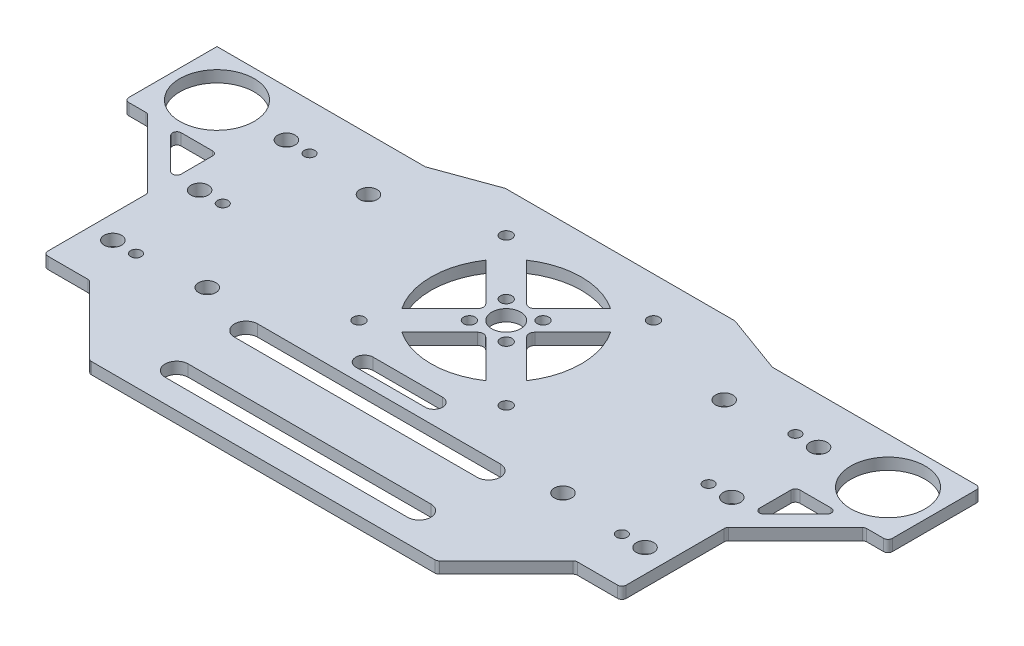
SolidWorks part; units mm, degrees
ref_plane "前视基准面" through (0, 0, 0) normal (0, 0, 1) x (1, 0, 0)
ref_plane "上视基准面" through (0, 0, 0) normal (0, 1, 0) x (1, 0, 0)
ref_plane "右视基准面" through (0, 0, 0) normal (1, 0, 0) x (0, 0, -1)
other "Configuration Table"
sketch "草图1" plane through (0, 0, 0) normal (0, 1, 0) x (1, 0, 0)
  line L0 (-50, 23) -> (50, 23)
  line L1 (50, 23) -> (50, -23)
  line L2 (50, -23) -> (-50, -23)
  line L3 (-50, -23) -> (-50, 23)
  line L5 (0, 23) -> (0, -23) construction
  line L6 (3.182, 10.182) -> (-3.182, 3.818) construction
  line L7 (7.253, 17.7886) -> (-10.7886, -0.253) construction
  line L8 (10.7886, 14.253) -> (-7.253, -3.7886) construction
  line L9 (10.7886, -0.253) -> (-7.253, 17.7886) construction
  line L10 (7.253, -3.7886) -> (-10.7886, 14.253) construction
  line L11 (-7.253, -3.7886) -> (10.7886, 14.253) construction
  line L12 (-10.7886, -0.253) -> (7.253, 17.7886) construction
  line L13 (-10.7886, 14.253) -> (7.253, -3.7886) construction
  line L14 (-7.253, 17.7886) -> (10.7886, -0.253) construction
  line L15 (10.7886, -0.253) -> (4.2426, 6.2929)
  line L16 (4.2426, 7.7071) -> (10.7886, 14.253)
  line L17 (7.253, 17.7886) -> (0.7071, 11.2426)
  line L18 (-0.7071, 11.2426) -> (-7.253, 17.7886)
  line L19 (-10.7886, 14.253) -> (-4.2426, 7.7071)
  line L20 (-4.2426, 6.2929) -> (-10.7886, -0.253)
  line L21 (-7.253, -3.7886) -> (-0.7071, 2.7574)
  line L22 (0.7071, 2.7574) -> (7.253, -3.7886)
  line L23 (-30, 23) -> (-19.848, 26.695)
  line L24 (-19.848, 26.695) -> (0.0265, 26.695)
  line L25 (30, 23) -> (19.848, 26.695)
  line L26 (19.848, 26.695) -> (-0.0265, 26.695)
  line L27 (-50, 23) -> (-66, 23)
  line L28 (-66, 23) -> (-66, 7)
  line L29 (-66, 7) -> (-50, 7)
  line L30 (-50, 7) -> (-50, 23)
  line L31 (-58, 7) -> (-50, -1)
  line L32 (-62, 7) -> (-50, -5)
  line L33 (-50, -1) -> (-50, -5)
  line L34 (-58, 7) -> (-62, 7)
  line L35 (58, 7) -> (62, 7)
  line L36 (50, -1) -> (50, -5)
  line L37 (62, 7) -> (50, -5)
  line L38 (58, 7) -> (50, -1)
  line L39 (50, 7) -> (50, 23)
  line L40 (66, 7) -> (50, 7)
  line L41 (66, 23) -> (66, 7)
  line L42 (50, 23) -> (66, 23)
  line L43 (-42, -23) -> (-30, -35)
  line L44 (-30, -35) -> (30, -35)
  line L45 (42, -23) -> (30, -35)
  line L46 (-42, -23) -> (42, -23)
  line L47 (-46, 23) -> (-46, -23) construction
  line L48 (-50, 0) -> (50, 0) construction
  line L49 (-6, -11.5) -> (6, -11.5) construction
  line L50 (-6, -10) -> (6, -10)
  line L51 (-20.9696, -17) -> (20.9696, -17) construction
  line L52 (-20.9696, -15) -> (20.9696, -15)
  line L53 (-20.9696, -19) -> (20.9696, -19)
  line L54 (-20.9696, -29) -> (20.9696, -29) construction
  line L55 (-20.9696, -27) -> (20.9696, -27)
  line L56 (-20.9696, -31) -> (20.9696, -31)
  line L57 (-6, -13) -> (6, -13)
  line L58 (-42, 15) -> (-42, 10.5355) construction
  circle A0 centre (0, 7) radius 2.5
  circle A1 centre (3.182, 10.182) radius 1
  circle A2 centre (3.182, 3.818) radius 1
  circle A3 centre (-3.182, 3.818) radius 1
  circle A4 centre (-3.182, 10.182) radius 1
  circle A5 centre (0, 7) radius 13
  circle A6 centre (12.7279, 19.7279) radius 1
  circle A7 centre (12.7279, -5.7279) radius 1
  circle A8 centre (-12.7279, -5.7279) radius 1
  circle A9 centre (-12.7279, 19.7279) radius 1
  arc A10 (-0.7071, 2.7574) -> (0.7071, 2.7574) centre (0, 2.0503) cw
  arc A11 (-4.2426, 7.7071) -> (-4.2426, 6.2929) centre (-4.9497, 7) cw
  arc A12 (0.7071, 11.2426) -> (-0.7071, 11.2426) centre (0, 11.9497) cw
  arc A13 (4.2426, 6.2929) -> (4.2426, 7.7071) centre (4.9497, 7) cw
  circle A15 centre (-58, 15) radius 6.425
  circle A16 centre (58, 15) radius 6.425
  circle A17 centre (-46, 15) radius 1.5
  circle A18 centre (-46, 0) radius 1.5
  circle A19 centre (-46, -15) radius 1.5
  circle A20 centre (46, -15) radius 1.5
  circle A21 centre (46, 0) radius 1.5
  circle A22 centre (46, 15) radius 1.5
  circle A23 centre (30.7465, 13.935) radius 1.5
  circle A24 centre (30.7465, -13.935) radius 1.5
  circle A25 centre (-30.7465, -13.935) radius 1.5
  circle A26 centre (-30.7465, 13.935) radius 1.5
  circle A27 centre (0, 7) radius 15
  arc A29 (-20.9696, -15) -> (-20.9696, -19) centre (-20.9696, -17) ccw
  arc A30 (20.9696, -19) -> (20.9696, -15) centre (20.9696, -17) ccw
  arc A31 (-20.9696, -27) -> (-20.9696, -31) centre (-20.9696, -29) ccw
  arc A32 (20.9696, -31) -> (20.9696, -27) centre (20.9696, -29) ccw
  arc A33 (-6, -10) -> (-6, -13) centre (-6, -11.5) ccw
  arc A34 (6, -13) -> (6, -10) centre (6, -11.5) ccw
  circle A35 centre (-42, 15) radius 0.925
  circle A36 centre (-42, 0) radius 0.925
  circle A37 centre (-42, -15) radius 0.925
  circle A38 centre (42, -15) radius 0.925
  circle A39 centre (42, 0) radius 0.925
  circle A40 centre (42, 15) radius 0.925
  point P5 (50, 0)
  point P6 (0, 23)
  point P42 (0, 3.4645)
  point P45 (-3.5355, 7)
  point P48 (0, 10.5355)
  point P51 (3.5355, 7)
  point P64 (-58, 23)
  point P66 (-66, 15)
  point P84 (0, -35)
  point P92 (-50, 0)
  point P111 (0, -11.5)
  point P116 (0, -17)
  point P122 (0, -29)
  dimension "D3" = 5
  dimension "D4" = 2
  dimension "D8" = 26
  dimension "D9" = 2
  dimension "D13" = 1
  dimension "D18" = 16
  dimension "D19" = 16
  dimension "D20" = 12.85
  dimension "D26" = 3
  dimension "D27" = 4
  dimension "D28" = 3
  dimension "D29" = 3
  dimension "D32" = 3
  dimension "D35" = 30
  dimension "D36" = 1.5
  dimension "D44" = 1.85
  dimension "D1" = 100
  dimension "D2" = 46
  dimension "D6" = 9
  dimension "D7" = 45
  dimension "D11" = 18
  dimension "D14" = 16
  dimension "D15" = 20
  dimension "D16" = 20
  dimension "D17" = 3.695
  dimension "D21" = 4
  dimension "D22" = 45
  dimension "D23" = 8
  dimension "D24" = 45
  dimension "D25" = 12
  dimension "D30" = 15
  dimension "D31" = 15
  dimension "D33" = 61.493
  dimension "D34" = 27.87
  dimension "D37" = 6
  dimension "D38" = 12
  dimension "D39" = 6
  dimension "D40" = 2
  dimension "D41" = 2
  dimension "D42" = 20.9696
  dimension "D43" = 5.5
  dimension "D45" = 4
  dimension "D47" = 46
  dimension "D46" = 3
  dimension "D5" = 4
  dimension "D10" = 4
  dimension "D12" = 4
extrude "凸台-拉伸1" add sketch "草图1" along normal blind 2
fillet "圆角1" radius 0.75 19 edges at (-50, 1, 5) (-62, 1, -7) (-42, 1, 23) (-30, 1, 35) (30, 1, 35) (42, 1, 23) (62, 1, -7) (50, 1, 5) (50, 1, 23) (50, 1, -7) (58, 1, -7) (66, 1, -7) (50, 1, 1) (66, 1, -23) (-50, 1, 1) (-58, 1, -7) (-50, 1, -7) (-50, 1, 23) (-66, 1, -7)
sketch "草图2" plane through (0, 2, 0) normal (0, 1, 0) x (1, 0, 0)
  text T0 "M3" font "@Microsoft YaHei UI" height 2
  text T1 "M2" font "@Microsoft YaHei UI" height 2
  text T2 "M3" font "@Microsoft YaHei UI" height 2
